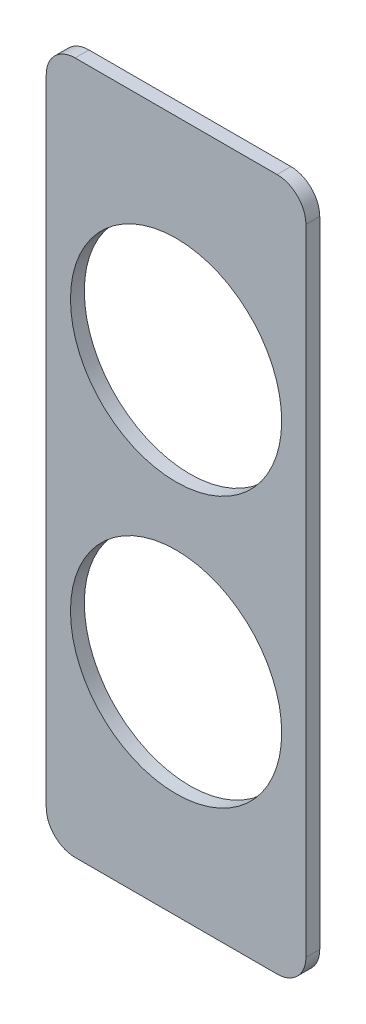
SolidWorks part; units mm, degrees
ref_plane "Front Plane" through (0, 0, 0) normal (0, 0, 1) x (1, 0, 0)
ref_plane "Top Plane" through (0, 0, 0) normal (0, 1, 0) x (1, 0, 0)
ref_plane "Right Plane" through (0, 0, 0) normal (1, 0, 0) x (0, 0, -1)
sketch "Sketch1" plane through (0, 0, 0) normal (0, 0, 1) x (1, 0, 0)
  line L1 (-22.225, 76.2) -> (22.225, 76.2)
  line L2 (-28.575, 69.85) -> (-28.575, -69.85)
  line L3 (-22.225, -76.2) -> (22.225, -76.2)
  line L4 (28.575, 69.85) -> (28.575, -69.85)
  line L5 (-28.575, 76.2) -> (28.575, -76.2) construction
  line L6 (-28.575, -76.2) -> (28.575, 76.2) construction
  circle A0 centre (0, 29.718) radius 23.241
  circle A1 centre (0, -29.718) radius 23.241
  arc A2 (-28.575, -69.85) -> (-22.225, -76.2) centre (-22.225, -69.85) ccw
  arc A3 (28.575, -69.85) -> (22.225, -76.2) centre (22.225, -69.85) cw
  arc A4 (28.575, 69.85) -> (22.225, 76.2) centre (22.225, 69.85) ccw
  arc A5 (-28.575, 69.85) -> (-22.225, 76.2) centre (-22.225, 69.85) cw
  point P0 (0, 0)
  point P10 (0, 0)
  dimension "D3" = 46.482
  dimension "D5" = 6.35
  dimension "D1" = 152.4
  dimension "D2" = 57.15
  dimension "D4" = 46.482
extrude "Boss-Extrude1" add sketch "Sketch1" against normal blind 3.048
equation "\"F\"= 600'Applied force"
equation "\"Yst\"= 39885.32'Yield strength"
equation "\"Sf\"= 4'Safety factor"
equation "\"def\"= .005'Deflection"
equation "\"Lst\"= 5'Length of strap"
equation "\"E\"= 10007604'Modulus of elasticity"
equation "\"Dst\"= ( ( \"F\" * \"Lst\" * \"Sf\" * 32 * 2 ) / ( \"Yst\" * 3.14159 ) ) ^ ( 1 / 3 )'Driven diameter of feauture A"
equation "\"Lftb\"= 4'Chosen length of feature B"
equation "\"hftb\"= ( ( \"F\" * \"Lftb\" * \"Sf\" * 6 * 2 ) / ( \"Dst\" * \"Yst\" ) ) ^ ( 1 / 2 )'Driven height of feature B"
equation "\"Bftc\"= 2.5'Base of feature C, from T-beam dim"
equation "\"hftc\"= ( ( \"F\" * \"Lst\" * \"Sf\" * 2 * 6 ) / ( \"Bftc\" * \"Yst\" ) ) ^ ( 1 / 2 )'Driven height of feature C"
equation "\"hftd\"= 1.5'Chosen height of feature D"
equation "\"cftd\"= \"hftd\" / 2'Neutral axis of feature D (distance)"
equation "\"bftd\"= ( \"F\" * \"Lst\" * \"cftd\" * \"Sf\" * 2 * 12 ) / ( \"Yst\" * ( \"hftd\" ^ 3 ) )'Driven base of feature D"
equation "\"bfte\"= 1'Base of feature E, from T-beam dim"
equation "\"hfte\"= ( ( \"F\" * \"Lst\" * \"Sf\" * 6 * 2 ) / ( \"Yst\" * \"bfte\" ) ) ^ ( 1 / 2 )'Driven height of feature E"
equation "\"hlink\"= 6'Chosen height of link"
equation "\"blink\"= 2.25'Chosen base of link"
equation "\"clink\"= 3'Neutral axis of link (distance)"
equation "\"tlink\"= ( \"F\" * \"hlink\" * \"clink\" * \"Sf\" * 12 * 2 ) / ( \"Yst\" * ( \"hlink\" ^ 3 ) )'Driven thickness of link"
